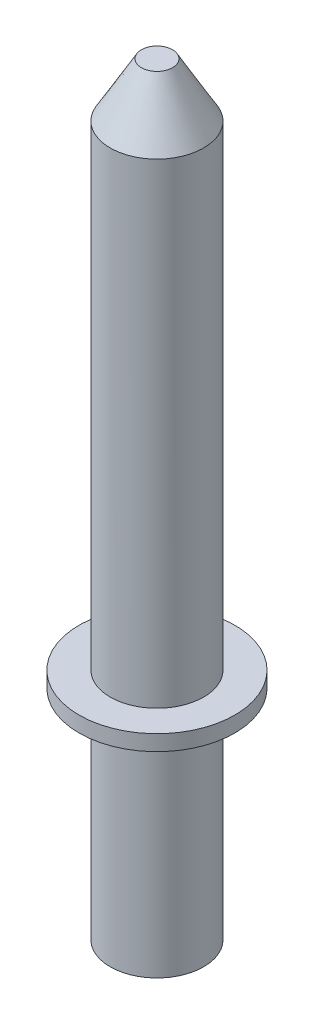
SolidWorks part; units mm, degrees
ref_plane "Front Plane" through (0, 0, 0) normal (0, 0, 1) x (1, 0, 0)
ref_plane "Top Plane" through (0, 0, 0) normal (0, 1, 0) x (1, 0, 0)
ref_plane "Right Plane" through (0, 0, 0) normal (1, 0, 0) x (0, 0, -1)
sketch "Sketch1" plane through (0, 0, 0) normal (0, 1, 0) x (1, 0, 0)
  circle A0 centre (0, 0) radius 1.5
  dimension "D1" = 3
extrude "Boss-Extrude1" add sketch "Sketch1" along normal blind 7
sketch "Sketch2" plane through (0, 7, 0) normal (0, 1, 0) x (1, 0, 0)
  circle A0 centre (0, 0) radius 2.5
  dimension "D1" = 5
extrude "Boss-Extrude2" add sketch "Sketch2" along normal blind 0.5
sketch "Sketch3" plane through (0, 7.5, 0) normal (0, 1, 0) x (1, 0, 0)
  circle A0 centre (0, 0) radius 1.5
  dimension "D1" = 3
extrude "Boss-Extrude3" add sketch "Sketch3" along normal blind 17
chamfer "Chamfer1" distance 1 angle 60 1 edges at (0, 24.5, 1.5)
